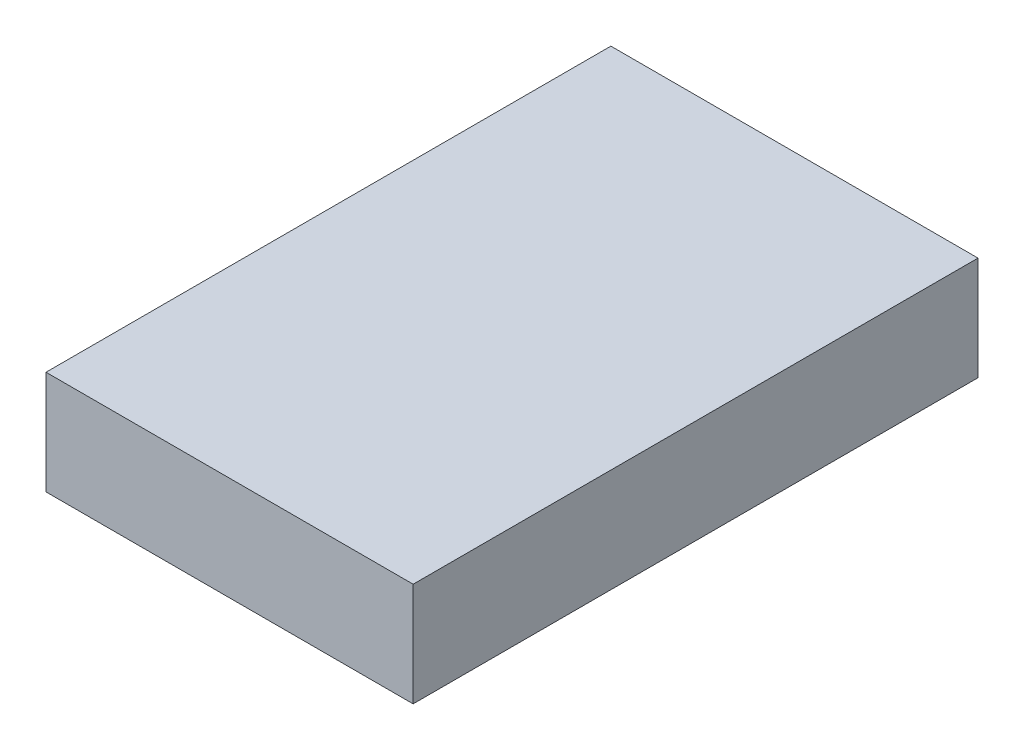
SolidWorks part; units mm, degrees
material "AISI 1020"
ref_plane "Front Plane" through (0, 0, 0) normal (0, 0, 1) x (1, 0, 0)
ref_plane "Top Plane" through (0, 0, 0) normal (0, 1, 0) x (1, 0, 0)
ref_plane "Right Plane" through (0, 0, 0) normal (1, 0, 0) x (0, 0, -1)
sketch "Sketch3" plane through (0, 0, 0) normal (0, 1, 0) x (1, 0, 0)
  line L1 (-129.4563, -199.4097) -> (0.5435, -199.4097)
  line L2 (-129.4563, -199.4097) -> (-129.4563, 0.595)
  line L3 (-129.4563, 0.595) -> (0.5435, 0.595)
  line L4 (0.5435, -199.4097) -> (0.5435, 0.595)
  line L5 (-129.4563, -199.4097) -> (0.5435, 0.595) construction
  line L6 (-129.4563, 0.595) -> (0.5435, -199.4097) construction
  point P0 (-64.4564, -99.4073)
  dimension "D1" = 129.9997
  dimension "D2" = 200.0048
extrude "Boss-Extrude1" add sketch "Sketch3" along normal blind 36.7
equation "\"width\"= 5.1181"
equation "\"length\"= 7.874204"
equation "\"depth\"= 1.444882"
equation "\"D1@Sketch3\"=\"width\""
equation "\"D1@Boss-Extrude1\"=\"depth\""
equation "\"D2@Sketch3\"=\"length\""
